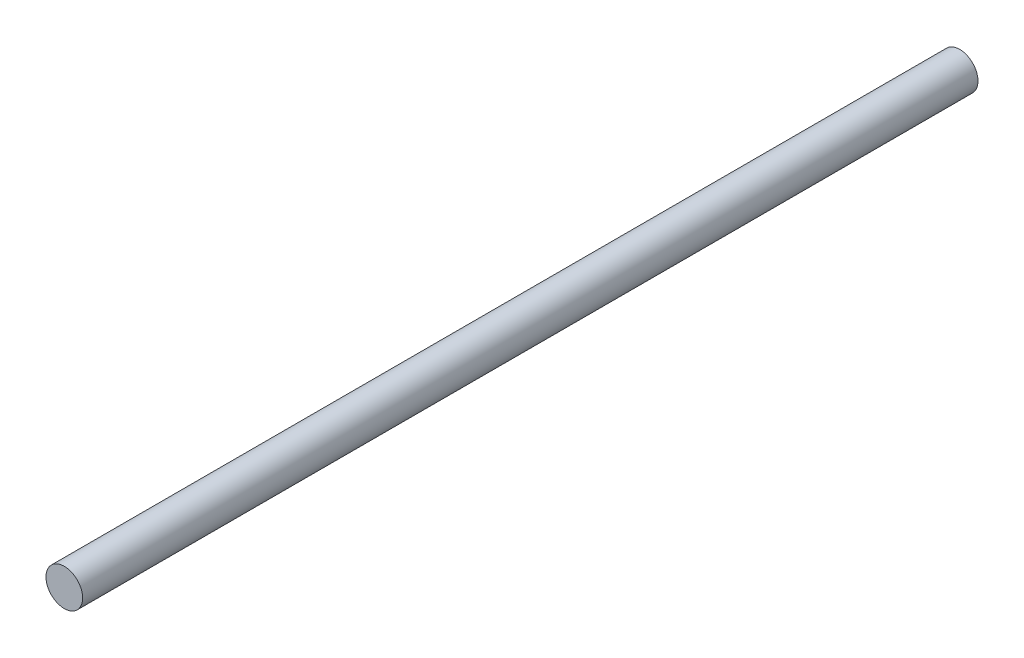
SolidWorks part; units mm, degrees
ref_plane "Front Plane" through (0, 0, 0) normal (0, 0, 1) x (1, 0, 0)
ref_plane "Top Plane" through (0, 0, 0) normal (0, 1, 0) x (1, 0, 0)
ref_plane "Right Plane" through (0, 0, 0) normal (1, 0, 0) x (0, 0, -1)
sketch "Sketch2" plane through (0, 0, 0) normal (0, 0, 1) x (1, 0, 0)
  circle A0 centre (0, 0) radius 2.15
  dimension "D1" = 4.3
extrude "Boss-Extrude1" add sketch "Sketch2" along normal blind 105
